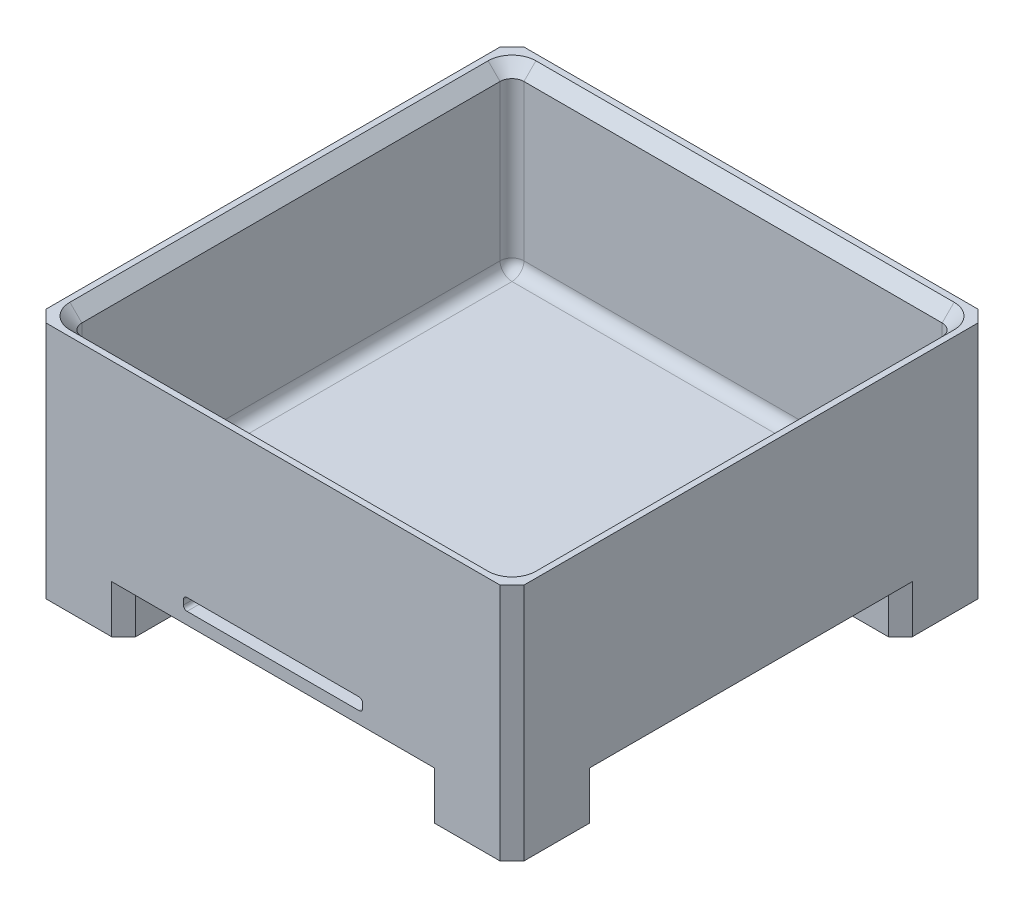
SolidWorks part; units mm, degrees
ref_plane "Front Plane" through (0, 0, 0) normal (0, 0, 1) x (1, 0, 0)
ref_plane "Top Plane" through (0, 0, 0) normal (0, 1, 0) x (1, 0, 0)
ref_plane "Right Plane" through (0, 0, 0) normal (1, 0, 0) x (0, 0, -1)
sketch "Sketch1" plane through (0, 0, 0) normal (0, 1, 0) x (1, 0, 0)
  line L1 (200, 200) -> (-200, 200)
  line L2 (200, 200) -> (200, -200)
  line L3 (200, -200) -> (-200, -200)
  line L4 (-200, 200) -> (-200, -200)
  line L5 (200, 200) -> (-200, -200) construction
  line L6 (200, -200) -> (-200, 200) construction
  point P0 (0, 0)
  dimension "D1" = 400
  dimension "D2" = 400
extrude "Boss-Extrude1" add sketch "Sketch1" along normal blind 200
sketch "Sketch2" plane through (0, 200, 0) normal (0, 1, 0) x (1, 0, 0)
  line L14 (-185, -185) -> (185, -185)
  line L15 (185, -185) -> (185, 185)
  line L16 (-185, 185) -> (-185, -185)
  line L17 (185, 185) -> (-185, 185)
  line L18 (-185, -185) -> (185, -185)
  line L19 (185, -185) -> (185, 185)
  line L20 (-185, 185) -> (-185, -185)
  line L21 (185, 185) -> (-185, 185)
  dimension "D1" = 15
extrude "Cut-Extrude1" cut sketch "Sketch2" against normal blind 150
fillet "Fillet1" radius 10 8 edges at (0, 50, -185) (185, 50, 0) (0, 50, 185) (-185, 50, 0) (185, 125, 185) (-185, 125, 185) (185, 125, -185) (-185, 125, -185)
chamfer "Chamfer1" distance 10 angle 45 12 edges at (0, 200, -185) (-182.0711, 200, -182.0711) (182.0711, 200, -182.0711) (185, 200, 0) (182.0711, 200, 182.0711) (0, 200, 185) (-182.0711, 200, 182.0711) (-185, 200, 0) (-200, 100, -200) (200, 100, -200) (200, 100, 200) (-200, 100, 200)
sketch "Sketch3" plane through (0, 0, 200) normal (0, 0, 1) x (1, 0, 0)
  line L1 (-72, 60) -> (72, 60)
  line L2 (-75, 57) -> (-75, 53)
  line L3 (-72, 50) -> (72, 50)
  line L4 (75, 57) -> (75, 53)
  line L5 (-75, 60) -> (75, 50) construction
  line L6 (-75, 50) -> (75, 60) construction
  arc A0 (-75, 53) -> (-72, 50) centre (-72, 53) ccw
  arc A1 (75, 53) -> (72, 50) centre (72, 53) cw
  arc A2 (75, 57) -> (72, 60) centre (72, 57) ccw
  arc A3 (-72, 60) -> (-75, 57) centre (-72, 57) ccw
  point P0 (0, 55)
  dimension "D4" = 3
  dimension "D1" = 150
  dimension "D2" = 10
  dimension "D3" = 50
extrude "Cut-Extrude2" cut sketch "Sketch3" against normal up to next
sketch "Sketch4" plane through (0, 0, 0) normal (0, -1, 0) x (1, 0, 0)
  line L0 (190, 125) -> (135, 125)
  line L1 (125, 135) -> (125, 190)
  line L2 (190, -125) -> (135, -125)
  line L3 (125, -135) -> (125, -190)
  line L4 (-125, 190) -> (-125, 135)
  line L5 (-135, 125) -> (-190, 125)
  line L6 (-190, -125) -> (-135, -125)
  line L7 (-125, -135) -> (-125, -190)
  line L28 (200, 135) -> (190, 125)
  line L29 (135, 125) -> (125, 135)
  line L30 (125, 190) -> (135, 200)
  line L31 (200, -135) -> (190, -125)
  line L32 (135, -125) -> (125, -135)
  line L33 (125, -190) -> (135, -200)
  line L34 (-125, -190) -> (-135, -200)
  line L35 (-135, -125) -> (-125, -135)
  line L36 (-200, -135) -> (-190, -125)
  line L37 (-190, 125) -> (-200, 135)
  line L38 (-125, 135) -> (-135, 125)
  line L39 (-135, 200) -> (-125, 190)
  line L40 (200, 135) -> (200, -135)
  line L41 (135, -200) -> (-135, -200)
  line L42 (-200, -135) -> (-200, 135)
  line L43 (-135, 200) -> (135, 200)
  point P2 (200, 125)
  point P9 (125, 125)
  point P10 (200, -125)
  point P11 (125, 200)
  point P12 (125, -125)
  point P13 (-125, 200)
  point P14 (125, -200)
  point P15 (-125, 125)
  point P16 (-200, 125)
  point P17 (-200, -125)
  point P18 (-125, -125)
  point P20 (-125, -200)
  dimension "D2" = 75
  dimension "D3" = 75
  dimension "D4" = 75
  dimension "D5" = 75
  dimension "D6" = 75
  dimension "D7" = 75
  dimension "D8" = 75
  dimension "D9" = 270
  dimension "D10" = 270
  dimension "D23" = 65
  dimension "D24" = 65
  dimension "D25" = 65
  dimension "D26" = 65
extrude "Cut-Extrude3" cut sketch "Sketch4" against normal blind 40
